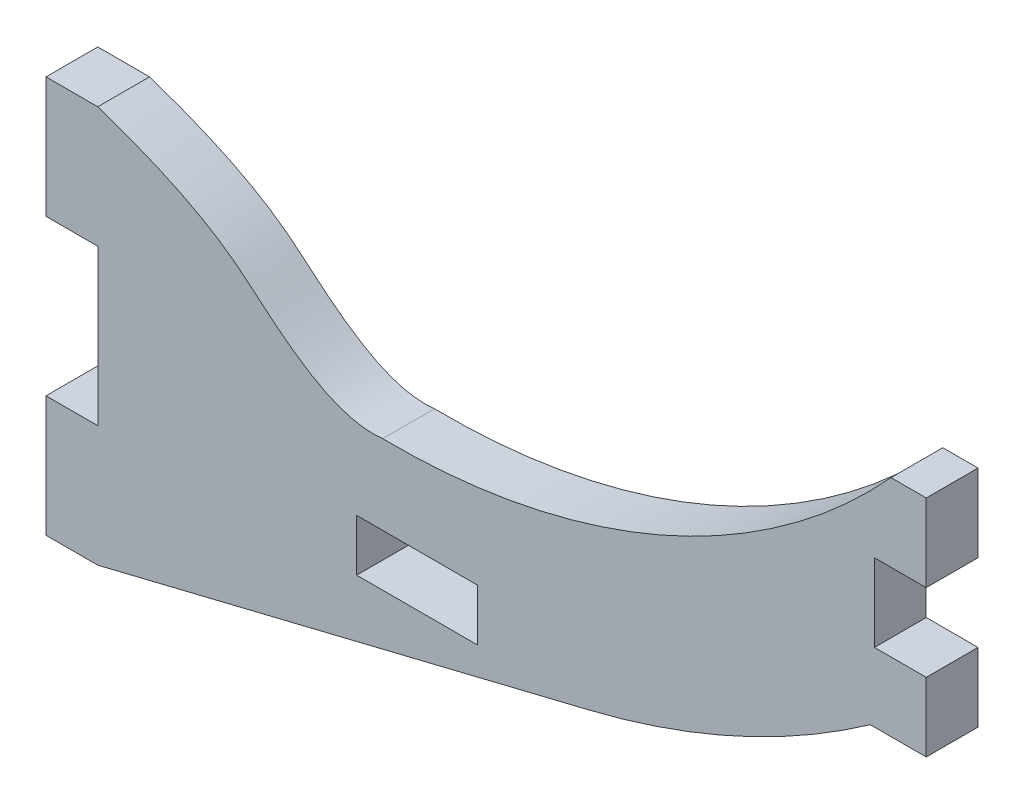
SolidWorks part; units mm, degrees
ref_plane "Alzado" through (0, 0, 0) normal (0, 0, 1) x (1, 0, 0)
ref_plane "Planta" through (0, 0, 0) normal (0, 1, 0) x (1, 0, 0)
ref_plane "Vista lateral" through (0, 0, 0) normal (1, 0, 0) x (0, 0, -1)
sketch "Croquis2" plane through (0, 0, 0) normal (0, 0, 1) x (1, 0, 0)
  line L1 (48, 16.8743) -> (48, 27.3743)
  line L2 (48, 27.3743) -> (45.9588, 27.3743)
  line L4 (0, 23.0034) -> (-3, 23.0034)
  line L5 (0, 23.0034) -> (0, 16.0034)
  line L6 (0, 23.0034) -> (0, 0)
  line L7 (28.5042, 6.9761) -> (0, 0)
  line L8 (0, 16.0034) -> (-3, 16.0034)
  line L9 (-3, 23.0034) -> (-3, 16.0034)
  line L10 (0, 0) -> (-3, 0)
  line L11 (0, 0) -> (0, 7)
  line L12 (0, 7) -> (-3, 7)
  line L13 (-3, 0) -> (-3, 7)
  line L14 (48, 18.3743) -> (45, 18.3743)
  line L15 (48, 18.3743) -> (48, 22.8743)
  line L16 (48, 22.8743) -> (45, 22.8743)
  line L17 (45, 18.3743) -> (45, 22.8743)
  arc A2 (15.1967, 14.6463) -> (45.9588, 27.3743) centre (17.0934, 53.6001) ccw
  arc A3 (28.5042, 6.9761) -> (48, 16.8743) centre (17.0934, 53.6001) ccw
  spline S0 degree 3 poles (0, 23.0034) (3.7689, 21.7485) (6.9474, 20.1031) (11.1476, 16.4082) (14.028, 14.3112) (16.5088, 14.6045) knots 0 0 0 0 0.366176 0.466176 1 1 1 1
  dimension "D1" = 23.0034
  dimension "D2" = 10.5
  dimension "D5" = 39
  dimension "D6" = 48
  dimension "D3" = 48
  dimension "D4" = 76.248
  dimension "D7" = 3
  dimension "D8" = 7
  dimension "D9" = 7
  dimension "D10" = 3
  dimension "D11" = 1.5
  dimension "D12" = 4.5
extrude "Saliente-Extruir1" add sketch "Croquis2" along normal blind 3 contours S0 L6 L7 A3 L1 L2 A2 | L5 L4 L9 L8 | L11 L10 L13 L12
sketch "Croquis3" plane through (0, 0, 0) normal (0, 0, 1) x (1, 0, 0)
  line L1 (0, 7) -> (26, 7) construction
  line L2 (0, 7) -> (0, 10) construction
  line L3 (0, 10) -> (26, 10) construction
  line L4 (26, 7) -> (26, 10) construction
  line L5 (15, 10) -> (22, 10)
  line L6 (15, 10) -> (15, 7)
  line L7 (15, 7) -> (22, 7)
  line L8 (22, 10) -> (22, 7)
  dimension "D1" = 3
  dimension "D2" = 26
  dimension "D3" = 7
  dimension "D4" = 15
extrude "Cortar-Extruir1" cut sketch "Croquis3" along normal blind 3
sketch "Croquis4" plane through (0, 0, 0) normal (0, 0, 1) x (1, 0, 0)
  line L0 (45, 18.3743) -> (45, 14.546)
  line L1 (44.7582, 14.3743) -> (48, 14.3743)
  line L2 (48, 16.8743) -> (48, 18.3743) construction
  line L3 (48, 14.3743) -> (48, 18.3743)
  line L4 (48, 18.3743) -> (45, 18.3743) construction
  line L5 (48, 18.3743) -> (45, 18.3743)
  arc A1 (28.5042, 6.9761) -> (48, 16.8743) centre (17.0934, 53.6001) ccw construction
  arc A2 (44.7582, 14.3743) -> (45, 14.546) centre (17.0934, 53.6001) ccw
extrude "Saliente-Extruir2" add sketch "Croquis4" along normal blind 3
